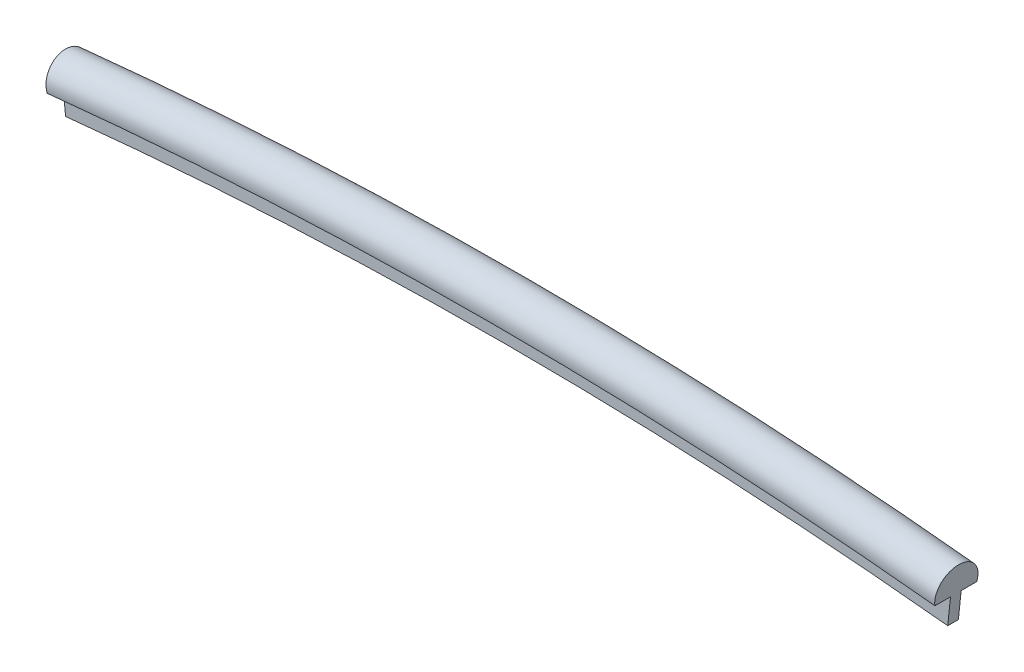
SolidWorks part; units mm, degrees
ref_plane "Front Plane" through (0, 0, 0) normal (0, 0, 1) x (1, 0, 0)
ref_plane "Top Plane" through (0, 0, 0) normal (0, 1, 0) x (1, 0, 0)
ref_plane "Right Plane" through (0, 0, 0) normal (1, 0, 0) x (0, 0, -1)
sketch "Sketch2" plane through (0, 0, 0) normal (1, 0, 0) x (0, 0, -1)
  line L0 (0, 241.3) -> (0, 0) construction
  line L2 (0, 241.3) -> (0, 239.8) construction
  line L3 (0, 239.8) -> (0.3, 239.8)
  line L4 (0, 239.8) -> (-0.3, 239.8)
  line L5 (-0.3, 239.8) -> (-0.3, 241.3)
  line L6 (0.3, 239.8) -> (0.3, 241.3)
  line L7 (0, 241.3) -> (0, 242.8) construction
  line L8 (-1.18, 241.3) -> (-0.3, 241.3)
  line L9 (0.3, 241.3) -> (1.18, 241.3)
  arc A0 (-1.18, 241.3) -> (1.18, 241.3) centre (0, 241.586) cw
  point P14 (0, 241.3)
ref_axis "Axis2" through (0, 0, 70.5976) along (0, 0, -1)
revolve "Revolve1" add sketch "Sketch2" angle 5.949 about axis through (0, 0, 70.5976) along (0, 0, -1)
